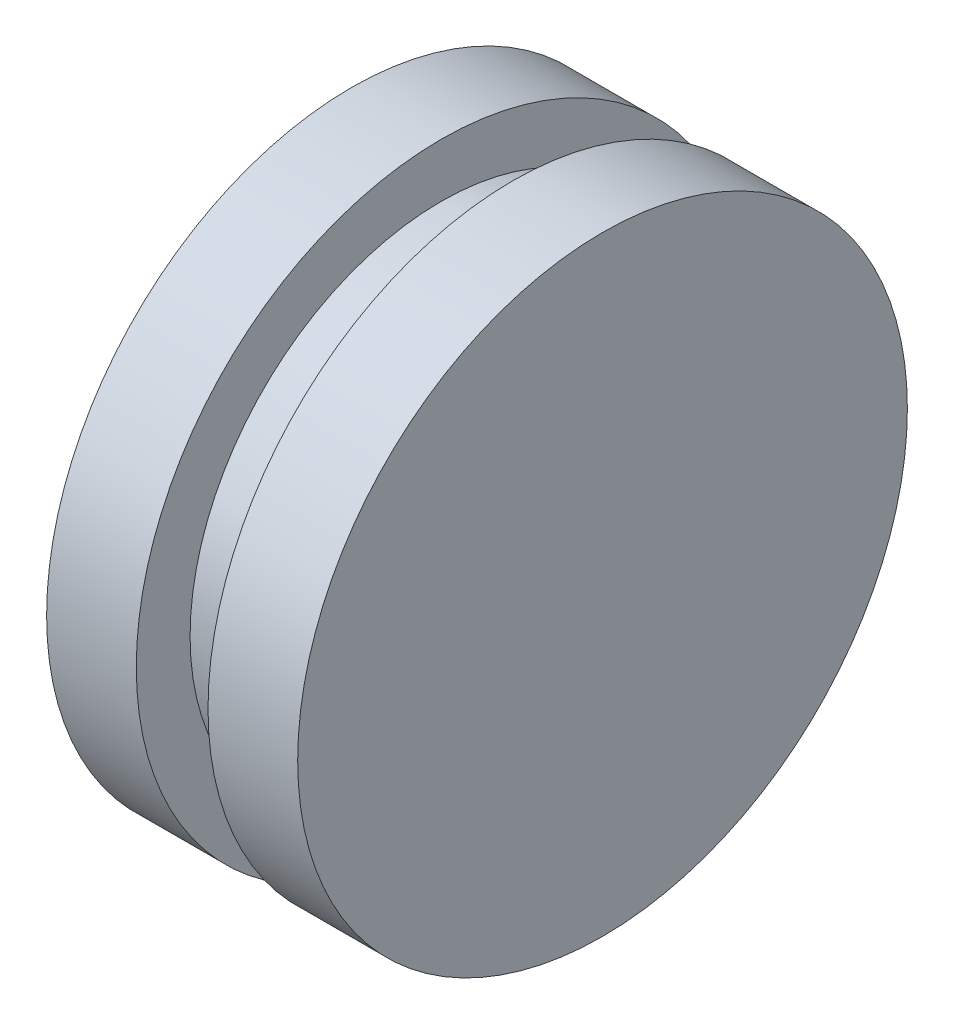
SolidWorks part; units mm, degrees
ref_plane "Front Plane" through (0, 0, 0) normal (0, 0, 1) x (1, 0, 0)
ref_plane "Top Plane" through (0, 0, 0) normal (0, 1, 0) x (1, 0, 0)
ref_plane "Right Plane" through (0, 0, 0) normal (1, 0, 0) x (0, 0, -1)
sketch "Sketch1" plane through (0, 0, 0) normal (0, 0, 1) x (1, 0, 0)
  line L0 (0, 0) -> (0, -17)
  line L1 (0, -17) -> (5, -17)
  line L2 (5, -17) -> (5, -14)
  line L3 (5, -14) -> (9, -14)
  line L4 (9, -14) -> (9, -17)
  line L7 (14, 0) -> (0, 0)
  line L10 (14, -17) -> (14, 0)
  line L11 (14, -17) -> (9, -17)
  dimension "D1" = 17
  dimension "D2" = 3
  dimension "D3" = 4
  dimension "D4" = 5
  dimension "D5" = 5
  dimension "D7" = 17
revolve "Revolve1" add sketch "Sketch1" angle 360 about L7
